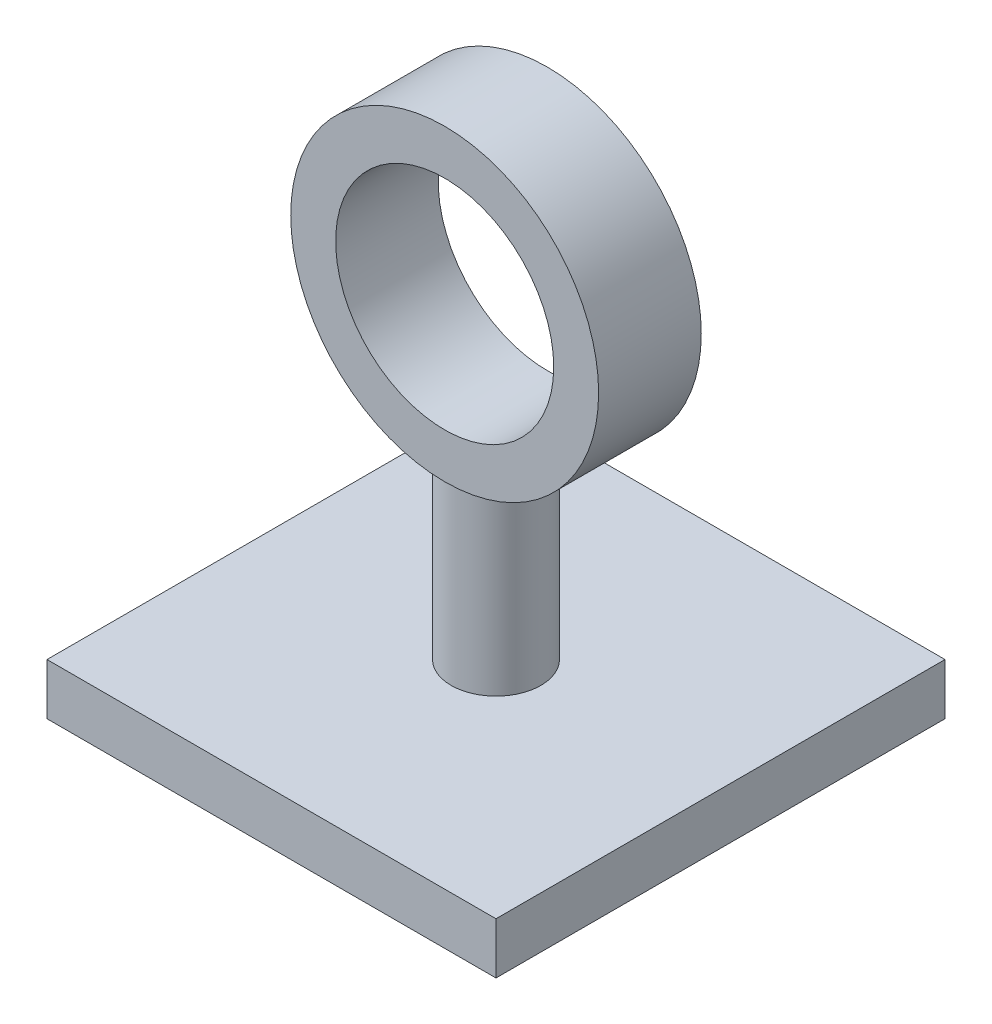
SolidWorks part; units mm, degrees
material "Alumina"
ref_plane "Front Plane" through (0, 0, 0) normal (0, 0, 1) x (1, 0, 0)
ref_plane "Top Plane" through (0, 0, 0) normal (0, 1, 0) x (1, 0, 0)
ref_plane "Right Plane" through (0, 0, 0) normal (1, 0, 0) x (0, 0, -1)
sketch "Sketch1" plane through (0, 0, 0) normal (0, 1, 0) x (1, 0, 0)
  line L1 (-35, 35) -> (35, 35)
  line L2 (-35, 35) -> (-35, -35)
  line L3 (-35, -35) -> (35, -35)
  line L4 (35, 35) -> (35, -35)
  line L5 (-35, 35) -> (35, -35) construction
  line L6 (-35, -35) -> (35, 35) construction
  point P0 (0, 0)
  dimension "D1" = 70
  dimension "D2" = 70
extrude "Boss-Extrude1" add sketch "Sketch1" along normal blind 8
sketch "Sketch2" plane through (0, 0, 0) normal (0, 1, 0) x (1, 0, 0)
  circle A0 centre (0, 0) radius 7
  dimension "D1" = 14
extrude "Boss-Extrude2" add sketch "Sketch2" along normal blind 36
sketch "Sketch3" plane through (0, 0, 0) normal (0, 0, 1) x (1, 0, 0)
  line L0 (0, 0) -> (0, 36) construction
  line L1 (7, 36) -> (-7, 36) construction
  line L2 (0, 0) -> (0, 60) construction
  circle A0 centre (0, 60) radius 24
  circle A1 centre (0, 60) radius 17
  dimension "D2" = 34
  dimension "D1" = 60
extrude "Boss-Extrude3" add sketch "Sketch3" along normal blind 8 and the other way blind 8 separate body
